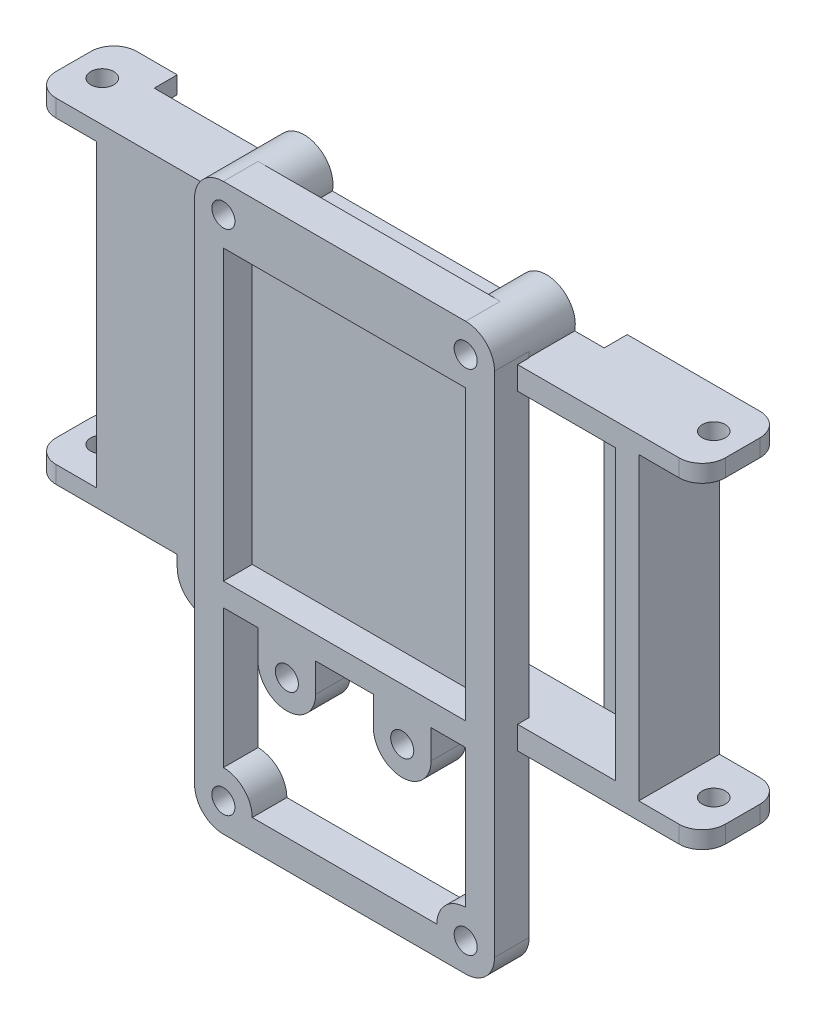
SolidWorks part; units mm, degrees
ref_plane "Front Plane" through (0, 0, 0) normal (0, 0, 1) x (1, 0, 0)
ref_plane "Top Plane" through (0, 0, 0) normal (0, 1, 0) x (1, 0, 0)
ref_plane "Right Plane" through (0, 0, 0) normal (1, 0, 0) x (0, 0, -1)
sketch "Sketch1" plane through (0, 0, 0) normal (0, 0, 1) x (1, 0, 0)
  line L0 (-13, 44) -> (-13, 0)
  line L1 (-10.5, 44) -> (10.5, 44) construction
  line L2 (-10.5, 44) -> (-10.5, 0) construction
  line L3 (-10.5, 0) -> (10.5, 0) construction
  line L4 (10.5, 44) -> (10.5, 0) construction
  line L5 (-10.5, 44) -> (10.5, 0) construction
  line L6 (-10.5, 0) -> (10.5, 44) construction
  line L7 (-10.5, -2.5) -> (10.5, -2.5)
  line L8 (13, 0) -> (13, 44)
  line L9 (10.5, 46.5) -> (-10.5, 46.5)
  line L10 (-10.5, 41.5) -> (-10.5, 2.5)
  line L11 (-8, 0) -> (8, 0)
  line L12 (10.5, 2.5) -> (10.5, 41.5)
  line L13 (8, 44) -> (-8, 44) construction
  line L14 (-10.5, 41.5) -> (10.5, 41.5)
  circle A0 centre (-10.5, 44) radius 1
  circle A1 centre (10.5, 44) radius 1
  circle A2 centre (10.5, 0) radius 1
  circle A3 centre (-10.5, 0) radius 1
  arc A4 (-10.5, 46.5) -> (-13, 44) centre (-10.5, 44) ccw
  arc A5 (8, 44) -> (10.5, 41.5) centre (10.5, 44) ccw construction
  arc A6 (10.5, -2.5) -> (13, 0) centre (10.5, 0) ccw
  arc A7 (-8, 0) -> (-10.5, 2.5) centre (-10.5, 0) ccw
  arc A8 (-10.5, 41.5) -> (-8, 44) centre (-10.5, 44) ccw construction
  arc A9 (13, 44) -> (10.5, 46.5) centre (10.5, 44) ccw
  arc A10 (10.5, 2.5) -> (8, 0) centre (10.5, 0) ccw
  arc A11 (-13, 0) -> (-10.5, -2.5) centre (-10.5, 0) ccw
  point P0 (0, 22)
  dimension "D3" = 2
  dimension "D4" = 5
  dimension "D1" = 44
  dimension "D2" = 21
extrude "ESP Bracket" add sketch "Sketch1" against normal blind 3
sketch "Sketch2" plane through (0, 0, -3) normal (0, 0, -1) x (-1, 0, 0)
  line L0 (-8.0505, 43.5) -> (8.0505, 43.5)
  line L1 (-21.5, 41.5) -> (21.5, 41.5)
  line L2 (-21.5, 41.5) -> (-21.5, 16.5)
  line L3 (-21.5, 16.5) -> (21.5, 16.5)
  line L4 (21.5, 41.5) -> (21.5, 26.5)
  line L5 (-21.5, 41.5) -> (21.5, 16.5) construction
  line L6 (-21.5, 16.5) -> (21.5, 41.5) construction
  line L7 (-23.5, 43.5) -> (-12.9495, 43.5)
  line L8 (-23.5, 43.5) -> (-23.5, 14.5)
  line L9 (-23.5, 14.5) -> (23.5, 14.5)
  line L10 (23.5, 43.5) -> (23.5, 26.5)
  line L11 (-23.5, 43.5) -> (23.5, 14.5) construction
  line L12 (-23.5, 14.5) -> (23.5, 43.5) construction
  line L13 (12.9495, 43.5) -> (23.5, 43.5)
  line L14 (-10.5, 41.5) -> (10.5, 41.5) construction
  line L15 (21.5, 16.5) -> (23.5, 16.5) construction
  line L16 (21.5, 26.5) -> (23.5, 26.5)
  line L17 (23.5, 16.5) -> (23.5, 14.5)
  line L18 (21.5, 16.5) -> (21.5, 18)
  line L19 (21.5, 18) -> (23.5, 18)
  line L20 (23.5, 18) -> (23.5, 16.5)
  circle A0 centre (-10.5, 44) radius 1 construction
  circle A1 centre (10.5, 44) radius 1 construction
  arc A4 (-8.0505, 43.5) -> (-12.9495, 43.5) centre (-10.5, 44) ccw
  arc A5 (-10.5, 46.5) -> (-13, 44) centre (-10.5, 44) ccw construction
  arc A6 (12.9495, 43.5) -> (8.0505, 43.5) centre (10.5, 44) ccw
  arc A7 (13, 44) -> (10.5, 46.5) centre (10.5, 44) ccw construction
  circle A8 centre (-10.5, 44) radius 1
  circle A9 centre (10.5, 44) radius 1
  point P0 (0, 29)
  point P9 (0, 29)
  dimension "D1" = 25
  dimension "D2" = 43
  dimension "D3" = 2
  dimension "D4" = 2
  dimension "D5" = 10
  dimension "D6" = 1.5
extrude "LoRa Holder Sides" add sketch "Sketch2" along normal blind 4
sketch "Sketch9" plane through (0, 0, -3) normal (0, 0, 1) x (1, 0, 0)
  line L1 (-10.5, 14.5) -> (10.5, 14.5)
  line L2 (-10.5, 14.5) -> (-10.5, 41.5)
  line L3 (-10.5, 41.5) -> (10.5, 41.5)
  line L4 (10.5, 14.5) -> (10.5, 41.5)
extrude "LoRa Backing (ADD MPU HOLE)" add sketch "Sketch9" along normal blind 0.5
sketch "Sketch4" plane through (0, 0, -7) normal (0, 0, -1) x (-1, 0, 0)
  line L0 (-23.5, 14.5) -> (23.5, 14.5) construction
  line L1 (-23.5, 43.5) -> (-15.5, 43.5)
  line L2 (-23.5, 43.5) -> (-23.5, 14.5)
  line L3 (-23.5, 14.5) -> (-15.5, 14.5)
  line L4 (-15.5, 43.5) -> (-15.5, 14.5)
  dimension "D1" = 8
extrude "LoRa Connector Cover" add sketch "Sketch4" along normal blind 2
sketch "Sketch6" plane through (0, 0, -3) normal (0, 0, 1) x (1, 0, 0)
  line L1 (-23.5, 43.5) -> (-13, 43.5)
  line L2 (-23.5, 43.5) -> (-23.5, 14.5)
  line L3 (-23.5, 14.5) -> (-13, 14.5)
  line L4 (-13, 43.5) -> (-13, 14.5)
  line L12 (13, 16.5) -> (13, 14.5)
  line L13 (13, 14.5) -> (23.5, 14.5)
  line L14 (23.5, 14.5) -> (23.5, 43.5)
  line L15 (23.5, 43.5) -> (13, 43.5)
  line L16 (13, 43.5) -> (13, 41.5)
  line L17 (13, 41.5) -> (21.5, 41.5)
  line L18 (21.5, 41.5) -> (21.5, 16.5)
  line L19 (21.5, 16.5) -> (13, 16.5)
  line L20 (13, 16.5) -> (13, 14.5)
  line L21 (13, 14.5) -> (23.5, 14.5)
  line L22 (23.5, 14.5) -> (23.5, 43.5)
  line L23 (23.5, 43.5) -> (13, 43.5)
  line L24 (13, 43.5) -> (13, 41.5)
  line L25 (13, 41.5) -> (21.5, 41.5)
  line L26 (21.5, 41.5) -> (21.5, 16.5)
  line L27 (21.5, 16.5) -> (13, 16.5)
  dimension "D1" = 0
extrude "Other Side LoRa Cover" add sketch "Sketch6" along normal blind 1
sketch "Sketch7" plane through (0, 0, -7) normal (0, 0, -1) x (-1, 0, 0)
  line L0 (13, 14.5) -> (13, 0) construction
  line L1 (-15.5, 14.5) -> (23.5, 14.5) construction
  line L7 (16.5, 16.5) -> (11.5, 16.5)
  line L11 (16.5, 13.5) -> (16.5, 16.5)
  line L12 (11.5, 13.5) -> (11.5, 16.5)
  line L13 (21.5, 16.5) -> (-15.5, 16.5) construction
  circle A0 centre (14, 13.5) radius 1
  arc A2 (11.5, 13.5) -> (16.5, 13.5) centre (14, 13.5) ccw
  dimension "D1" = 2
  dimension "D2" = 5
extrude "LoRa Clamp Third Screwhole" add sketch "Sketch7" against normal up to surface (5 mm away) up to face at (-18.25, 29, -2)
sketch "Sketch10" plane through (0, 0, 0) normal (0, 0, 1) x (1, 0, 0)
  line L0 (-10.5, 41.5) -> (-10.5, 14.5) construction
  line L1 (-10.5, 16.5) -> (10.5, 16.5)
  line L2 (-10.5, 16.5) -> (-10.5, 14.5)
  line L3 (-10.5, 14.5) -> (-7.5, 14.5)
  line L4 (10.5, 16.5) -> (10.5, 14.5)
  line L5 (-7.5, 12) -> (-7.5, 14.5)
  line L6 (-2.5, 12) -> (-2.5, 14.5)
  line L7 (2.5, 12) -> (2.5, 14.5)
  line L8 (7.5, 12) -> (7.5, 14.5)
  line L9 (-2.5, 14.5) -> (2.5, 14.5)
  line L10 (7.5, 14.5) -> (10.5, 14.5)
  line L11 (-10.5, 41.5) -> (-10.5, 2.5) construction
  circle A0 centre (-5, 12) radius 1
  circle A1 centre (5, 12) radius 1
  arc A2 (2.5, 12) -> (7.5, 12) centre (5, 12) ccw
  arc A3 (-7.5, 12) -> (-2.5, 12) centre (-5, 12) ccw
  dimension "D2" = 2
  dimension "D3" = 5
  dimension "D1" = 2
  dimension "D4" = 10
  dimension "D5" = 5.5
extrude "Barometer Mount" add sketch "Sketch10" against normal up to surface (3 mm away) up to face at (-9.5, 0, -3)
sketch "Sketch11" plane through (0, 0, -9) normal (0, 0, -1) x (-1, 0, 0)
  line L1 (-23.5, 43.5) -> (-29, 43.5)
  line L2 (-23.5, 43.5) -> (-23.5, 42)
  line L3 (-23.5, 42) -> (-29, 42)
  line L4 (-29, 43.5) -> (-29, 42)
  line L5 (-23.5, 14.5) -> (-29, 14.5)
  line L6 (-23.5, 14.5) -> (-23.5, 16)
  line L7 (-23.5, 16) -> (-29, 16)
  line L8 (-29, 14.5) -> (-29, 16)
  line L9 (23.5, 14.5) -> (29, 14.5)
  line L10 (23.5, 14.5) -> (23.5, 16)
  line L11 (23.5, 16) -> (29, 16)
  line L12 (29, 14.5) -> (29, 16)
  line L13 (23.5, 43.5) -> (29, 43.5)
  line L14 (23.5, 43.5) -> (23.5, 42)
  line L15 (23.5, 42) -> (29, 42)
  line L16 (29, 43.5) -> (29, 42)
  dimension "D1" = 5.5
  dimension "D2" = 5.5
  dimension "D3" = 1.5
  dimension "D4" = 1.5
extrude "All tabs extrude sideways" add sketch "Sketch11" against normal up to surface (7 mm away) up to face at (-16.5774, 20.8453, -2)
sketch "Sketch14" plane through (0, 43.5, 0) normal (0, 1, 0) x (1, 0, 0)
  line L0 (-23.5, 7) -> (-23.5, 9) construction
  line L1 (29, 2) -> (29, 9) construction
  circle A0 centre (-26.5, 5.5) radius 1
  circle A1 centre (26.5, 5.5) radius 1
  point P8 (29, 5.5)
  dimension "D1" = 2
  dimension "D2" = 3
  dimension "D3" = 3
extrude "Screwhole cut" cut sketch "Sketch14" against normal through all both and the other way through all
fillet "Screwhole tab fillets" radius 2 8 edges at (29, 15.25, -2) (29, 15.25, -9) (29, 42.75, -2) (29, 42.75, -9) (-29, 15.25, -2) (-29, 15.25, -9) (-29, 42.75, -2) (-29, 42.75, -9)
